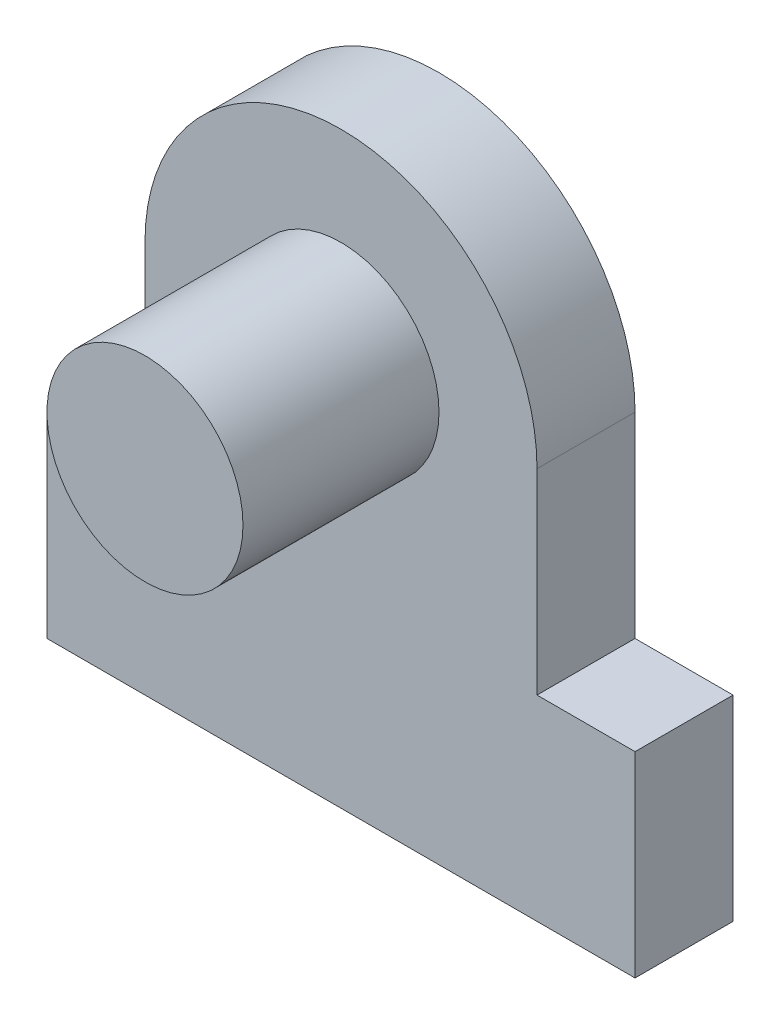
SolidWorks part; units mm, degrees
material "Stainless Steel (ferritic)"
ref_plane "Front Plane" through (0, 0, 0) normal (0, 0, 1) x (1, 0, 0)
ref_plane "Top Plane" through (0, 0, 0) normal (0, 1, 0) x (1, 0, 0)
ref_plane "Right Plane" through (0, 0, 0) normal (1, 0, 0) x (0, 0, -1)
sketch "Sketch1" plane through (0, 0, 0) normal (0, 0, 1) x (1, 0, 0)
  line L0 (-30, 0) -> (30, 0)
  line L1 (30, 0) -> (30, 20)
  line L2 (30, 20) -> (20, 20)
  line L3 (20, 20) -> (20, 40)
  line L4 (0, 0) -> (0, 40) construction
  line L5 (-30, 0) -> (-30, 20)
  line L6 (-30, 20) -> (-20, 20)
  line L7 (-20, 20) -> (-20, 40)
  arc A0 (20, 40) -> (-20, 40) centre (0, 40) ccw
  dimension "D5" = 20
  dimension "D1" = 60
  dimension "D2" = 20
  dimension "D3" = 10
  dimension "D4" = 20
extrude "Boss-Extrude1" add sketch "Sketch1" along normal blind 10
sketch "Sketch2" plane through (0, 0, 10) normal (0, 0, 1) x (1, 0, 0)
  circle A0 centre (0, 40) radius 10
  dimension "D1" = 20
extrude "Boss-Extrude2" add sketch "Sketch2" along normal blind 20
